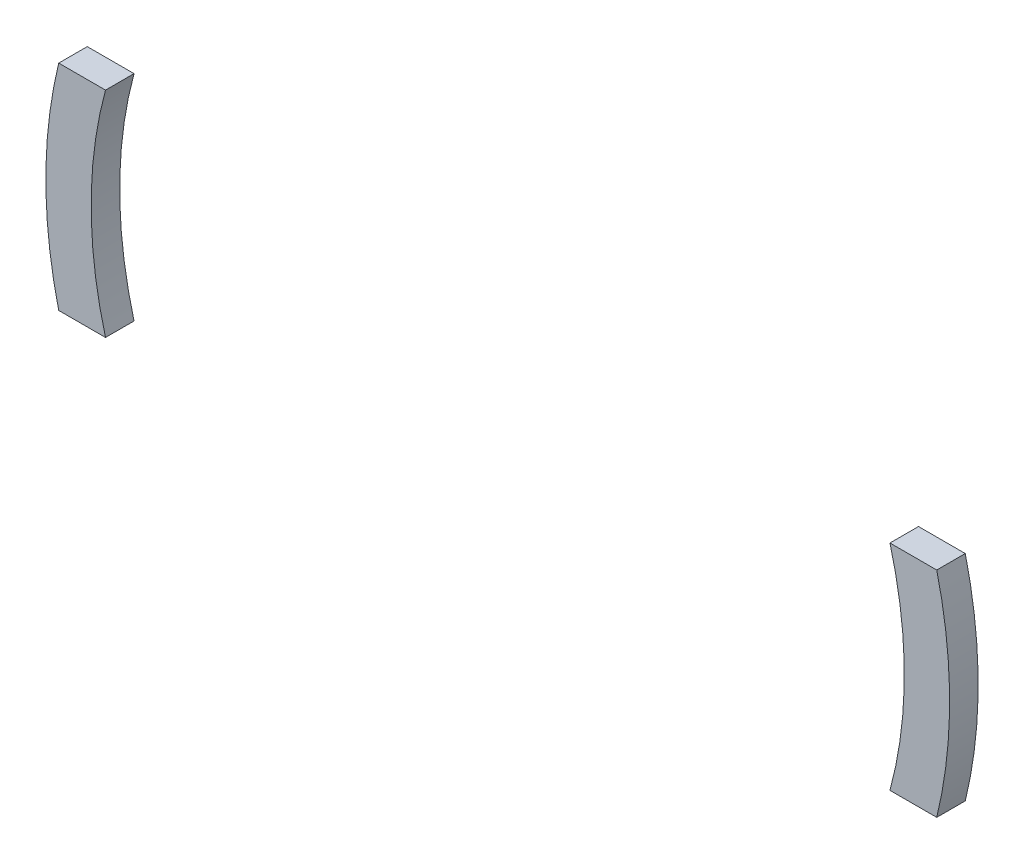
SolidWorks part; units mm, degrees
ref_plane "Front Plane" through (0, 0, 0) normal (0, 0, 1) x (1, 0, 0)
ref_plane "Top Plane" through (0, 0, 0) normal (0, 1, 0) x (1, 0, 0)
ref_plane "Right Plane" through (0, 0, 0) normal (1, 0, 0) x (0, 0, -1)
sketch "Sketch1" plane through (0, 0, 0) normal (0, 0, 1) x (1, 0, 0)
  line L0 (-39.0757, 9.5352) -> (-34.9113, 9.5352)
  line L2 (-39.0757, -9.5352) -> (-34.9113, -9.5352)
  line L3 (34.9113, -9.5352) -> (39.0757, -9.5352)
  line L4 (34.9113, 9.5352) -> (39.0757, 9.5352)
  arc A0 (-34.9113, 9.5352) -> (-34.9113, -9.5352) centre (0, 0) ccw
  arc A1 (-39.0757, 9.5352) -> (-39.0757, -9.5352) centre (0, 0) ccw
  arc A2 (39.0757, -9.5352) -> (39.0757, 9.5352) centre (0, 0) ccw
  arc A3 (34.9113, -9.5352) -> (34.9113, 9.5352) centre (0, 0) ccw
extrude "Boss-Extrude1" add sketch "Sketch1" along normal blind 2.54
